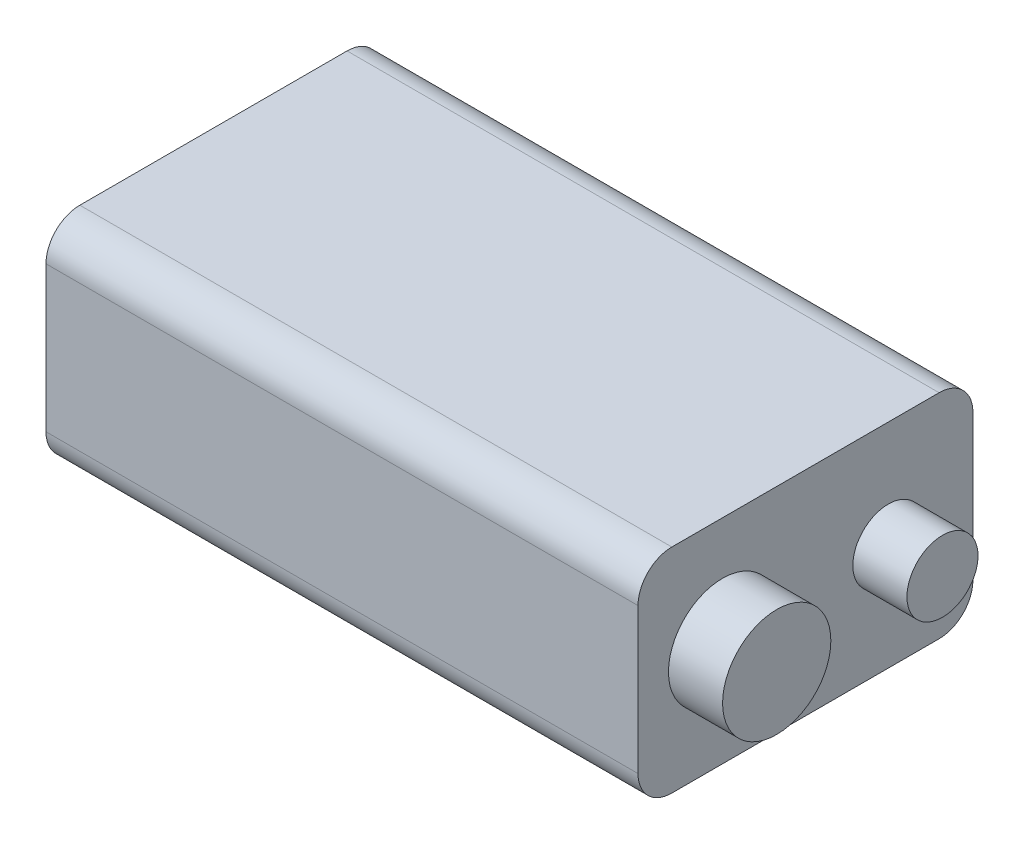
SolidWorks part; units mm, degrees
ref_plane "Front Plane" through (0, 0, 0) normal (0, 0, 1) x (1, 0, 0)
ref_plane "Top Plane" through (0, 0, 0) normal (0, 1, 0) x (1, 0, 0)
ref_plane "Right Plane" through (0, 0, 0) normal (1, 0, 0) x (0, 0, -1)
sketch "Sketch1" plane through (0, 0, 0) normal (0, 1, 0) x (1, 0, 0)
  line L1 (-22.225, 12.573) -> (22.225, 12.573)
  line L2 (-22.225, 12.573) -> (-22.225, -12.573)
  line L3 (-22.225, -12.573) -> (22.225, -12.573)
  line L4 (22.225, 12.573) -> (22.225, -12.573)
  line L5 (-22.225, 12.573) -> (22.225, -12.573) construction
  line L6 (-22.225, -12.573) -> (22.225, 12.573) construction
  point P0 (0, 0)
  dimension "D1" = 44.45
  dimension "D2" = 25.146
extrude "Boss-Extrude1" add sketch "Sketch1" along normal blind 16.002
fillet "Fillet1" radius 2.54 4 edges at (0, 0, -12.573) (0, 0, 12.573) (0, 16.002, -12.573) (0, 16.002, 12.573)
sketch "Sketch2" plane through (22.225, 0, 0) normal (1, 0, 0) x (0, 0, -1)
  line L0 (-12.573, 8.001) -> (12.573, 8.001) construction
  line L1 (-12.573, 13.462) -> (-12.573, 2.54) construction
  line L2 (12.573, 13.462) -> (12.573, 2.54) construction
  line L3 (0, 16.002) -> (0, 0) construction
  line L4 (-10.033, 16.002) -> (10.033, 16.002) construction
  line L5 (-10.033, 0) -> (10.033, 0) construction
  circle A0 centre (-6.223, 8.001) radius 4.064
  circle A1 centre (6.223, 8.001) radius 2.667
  dimension "D1" = 12.446
  dimension "D2" = 8.128
  dimension "D3" = 5.334
extrude "Boss-Extrude2" add sketch "Sketch2" along normal blind 4.064
